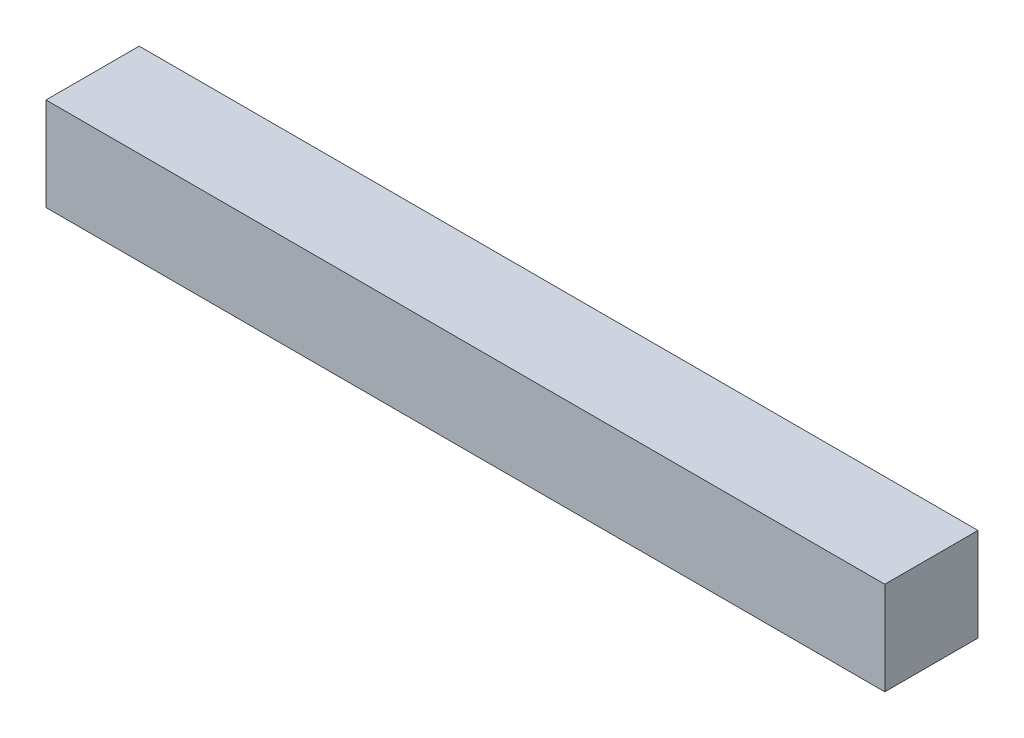
SolidWorks part; units mm, degrees
ref_plane "Front Plane" through (0, 0, 0) normal (0, 0, 1) x (1, 0, 0)
ref_plane "Top Plane" through (0, 0, 0) normal (0, 1, 0) x (1, 0, 0)
ref_plane "Right Plane" through (0, 0, 0) normal (1, 0, 0) x (0, 0, -1)
sketch "Sketch4" plane through (0, 0, 0) normal (0, 0, 1) x (1, 0, 0)
  line L1 (164.4146, 24.0881) -> (50.1146, 24.0881)
  line L2 (164.4146, 24.0881) -> (164.4146, 11.3881)
  line L3 (164.4146, 11.3881) -> (50.1146, 11.3881)
  line L4 (50.1146, 24.0881) -> (50.1146, 11.3881)
  dimension "D1" = 114.3
  dimension "D2" = 12.7
extrude "Boss-Extrude1" add sketch "Sketch4" along normal blind 12.7
shell "Shell4" thickness 2.54
